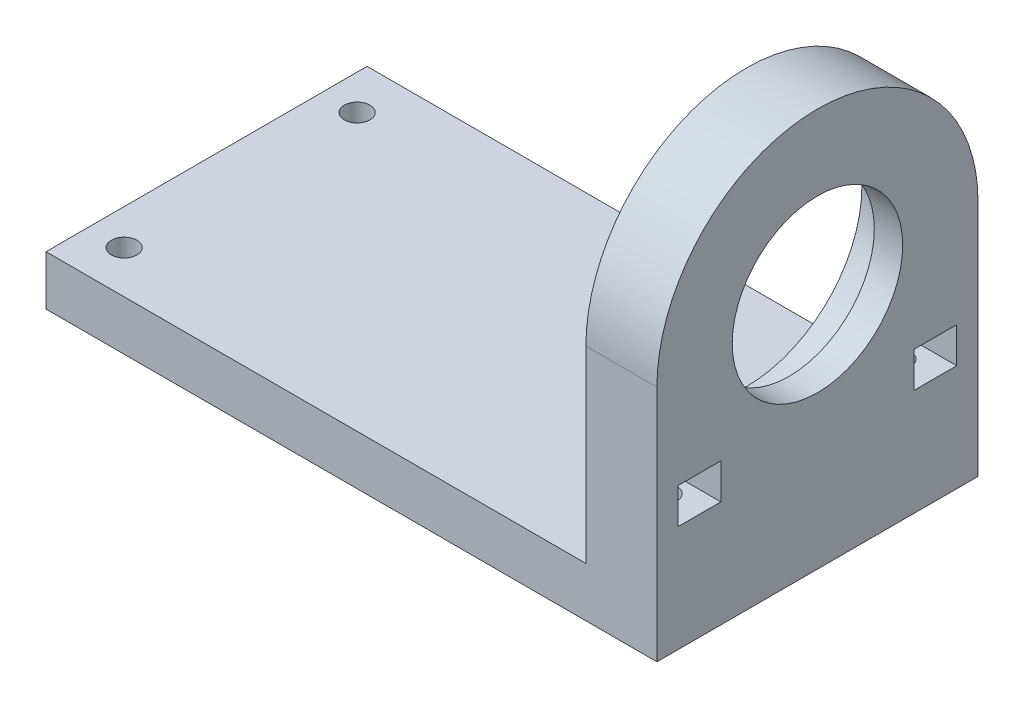
SolidWorks part; units mm, degrees
ref_plane "前视基准面" through (0, 0, 0) normal (0, 0, 1) x (1, 0, 0)
ref_plane "上视基准面" through (0, 0, 0) normal (0, 1, 0) x (1, 0, 0)
ref_plane "右视基准面" through (0, 0, 0) normal (1, 0, 0) x (0, 0, -1)
sketch "草图1" plane through (0, 0, 0) normal (0, 1, 0) x (1, 0, 0)
  line L1 (-43, -26) -> (43, -26)
  line L2 (-43, -26) -> (-43, 19.2)
  line L3 (-43, 19.2) -> (43, 19.2)
  line L4 (43, -26) -> (43, 19.2)
  dimension "D1" = 86
  dimension "D2" = 45.2
  dimension "D3" = 26
  dimension "D4" = 43
extrude "凸台-拉伸1" add sketch "草图1" along normal blind 7
ref_plane "基准面1" through (0, 7, 0) normal (0, 1, 0) x (1, 0, 0)
ref_plane "基准面2" through (43, 0, 0) normal (1, 0, 0) x (0, 0, -1)
sketch "草图4" plane through (43, 0, 0) normal (1, 0, 0) x (0, 0, -1)
  line L0 (-3.4, 33.5) -> (-3.4, 0) construction
  line L1 (19.2, 0) -> (-26, 0)
  line L2 (19.2, 0) -> (19.2, 33.5)
  line L4 (-26, 0) -> (-26, 33.5)
  line L5 (-23, 15) -> (-17, 15)
  line L6 (-23, 15) -> (-23, 20)
  line L7 (-23, 20) -> (-17, 20)
  line L8 (-17, 15) -> (-17, 20)
  line L9 (16.2, 20) -> (10.2, 20)
  line L10 (10.2, 15) -> (10.2, 20)
  line L11 (16.2, 15) -> (10.2, 15)
  line L12 (16.2, 15) -> (16.2, 20)
  arc A0 (19.2, 33.5) -> (-26, 33.5) centre (-3.4, 33.5) ccw
  circle A1 centre (-3.4, 33.5) radius 12
  dimension "D4" = 22.6
  dimension "D5" = 24
  dimension "D1" = 33.5
  dimension "D2" = 45.2
  dimension "D3" = 33.5
  dimension "D6" = 5
  dimension "D7" = 6
  dimension "D8" = 3
  dimension "D9" = 15
extrude "凸台-拉伸2" add sketch "草图4" against normal blind 10
ref_plane "基准面3" through (33, 0, 0) normal (-1, 0, 0) x (0, 0, 1)
sketch "草图5" plane through (33, 0, 0) normal (-1, 0, 0) x (0, 0, 1)
  circle A0 centre (3.4, 33.5) radius 16.25
  dimension "D1" = 32.5
extrude "切除-拉伸1" cut sketch "草图5" against normal blind 6
sketch "草图6" plane through (0, 0, 0) normal (0, 1, 0) x (1, 0, 0)
  line L0 (43, -3.5751) -> (-43, -3.4) construction
  line L1 (43, -26) -> (43, 19.2) construction
  line L2 (-43, 19.2) -> (-43, -26) construction
  line L3 (-43, -26) -> (43, -26) construction
  circle A0 centre (38, -20) radius 1.8
  circle A1 centre (38.0669, 12.8701) radius 1.8
  dimension "D1" = 3.6
  dimension "D2" = 6
  dimension "D3" = 5
extrude "切除-拉伸2" cut sketch "草图6" along normal blind 20
sketch "草图7" plane through (0, 0, 0) normal (0, 1, 0) x (1, 0, 0)
  line L0 (43, -26) -> (43, 19.2) construction
  line L1 (43, -3.4) -> (-43, -3.4) construction
  line L2 (-43, 19.2) -> (-43, -26) construction
  circle A0 centre (38, -20) radius 3.5
  circle A1 centre (38, 13.2) radius 3.5
  dimension "D1" = 7
extrude "切除-拉伸3" cut sketch "草图7" along normal blind 3.5
sketch "草图8" plane through (0, 7, 0) normal (0, 1, 0) x (1, 0, 0)
  line L1 (-43, 19.2) -> (48.3867, 19.2)
  line L2 (-43, 19.2) -> (-43, -32.8941)
  line L3 (-43, -32.8941) -> (48.3867, -32.8941)
  line L4 (48.3867, 19.2) -> (48.3867, -32.8941)
  dimension "D1" = 52.0941
  dimension "D2" = 91.3867
ref_plane "基准面4" through (0, 0, 0) normal (-1, 0, 0) x (0, 0, 1)
mirror "镜向1" about plane through (0, 0, 0) normal (-1, 0, 0) of "切除-拉伸2", "切除-拉伸3"
